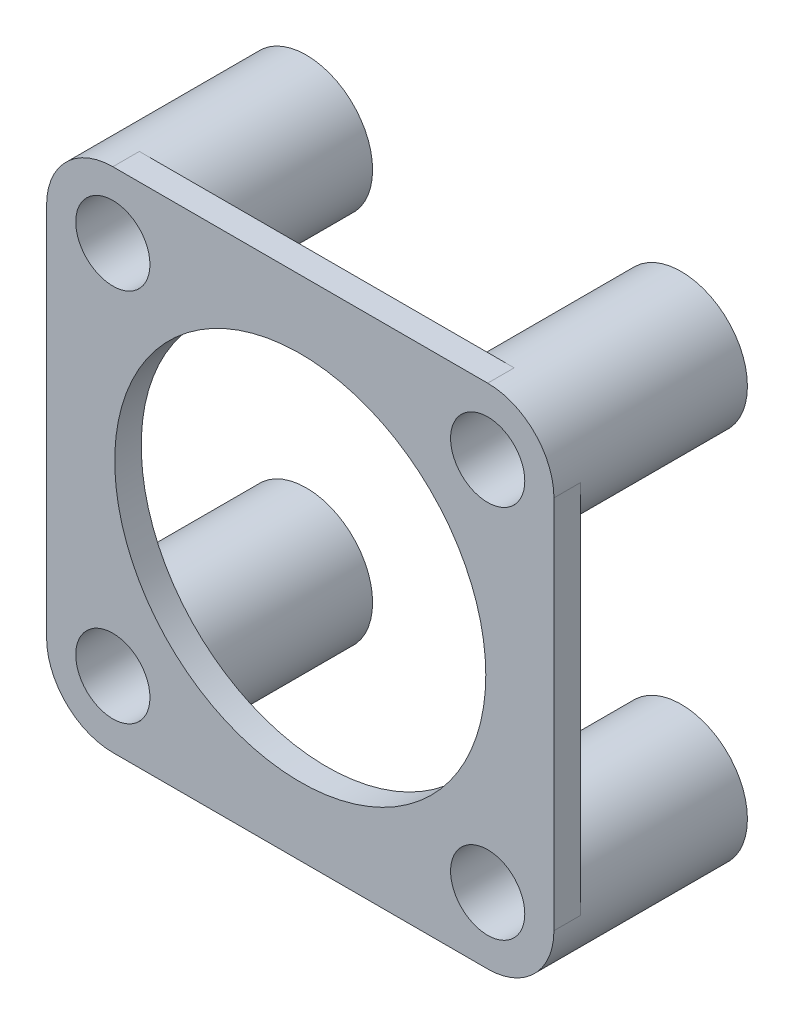
SolidWorks part; units mm, degrees
ref_plane "Front Plane" through (0, 0, 0) normal (0, 0, 1) x (1, 0, 0)
ref_plane "Top Plane" through (0, 0, 0) normal (0, 1, 0) x (1, 0, 0)
ref_plane "Right Plane" through (0, 0, 0) normal (1, 0, 0) x (0, 0, -1)
sketch "Sketch1" plane through (0, 0, 0) normal (0, 0, 1) x (1, 0, 0)
  line L1 (7.0711, -7.0711) -> (-7.0711, -7.0711) construction
  line L2 (7.0711, -7.0711) -> (7.0711, 7.0711) construction
  line L3 (7.0711, 7.0711) -> (-7.0711, 7.0711) construction
  line L4 (-7.0711, -7.0711) -> (-7.0711, 7.0711) construction
  line L5 (7.0711, -7.0711) -> (-7.0711, 7.0711) construction
  line L6 (7.0711, 7.0711) -> (-7.0711, -7.0711) construction
  circle A0 centre (-7.0711, 7.0711) radius 2.5
  circle A1 centre (7.0711, 7.0711) radius 2.5
  circle A2 centre (7.0711, -7.0711) radius 2.5
  circle A3 centre (-7.0711, -7.0711) radius 2.5
  circle A4 centre (-7.0711, 7.0711) radius 1.4
  circle A5 centre (7.0711, 7.0711) radius 1.4
  circle A6 centre (7.0711, -7.0711) radius 1.4
  circle A7 centre (-7.0711, -7.0711) radius 1.4
  point P0 (0, 0)
  dimension "D2" = 5
  dimension "D3" = 2.8
  dimension "D1" = 20
extrude "Boss-Extrude1" add sketch "Sketch1" along normal blind 6.3
sketch "Sketch2" plane through (0, 0, 6.3) normal (0, 0, 1) x (1, 0, 0)
  line L0 (-9.5711, 7.0711) -> (-9.5711, -7.0711)
  line L1 (-7.0711, -9.5711) -> (7.0711, -9.5711)
  line L2 (9.5711, -7.0711) -> (9.5711, 7.0711)
  line L3 (7.0711, 9.5711) -> (-7.0711, 9.5711)
  circle A0 centre (-7.0711, 7.0711) radius 2.5 construction
  circle A1 centre (-7.0711, -7.0711) radius 2.5 construction
  circle A2 centre (7.0711, -7.0711) radius 2.5 construction
  circle A3 centre (7.0711, 7.0711) radius 2.5 construction
  arc A4 (-9.5711, -7.0711) -> (-7.0711, -9.5711) centre (-7.0711, -7.0711) ccw
  arc A5 (7.0711, -9.5711) -> (9.5711, -7.0711) centre (7.0711, -7.0711) ccw
  arc A6 (9.5711, 7.0711) -> (7.0711, 9.5711) centre (7.0711, 7.0711) ccw
  arc A7 (-7.0711, 9.5711) -> (-9.5711, 7.0711) centre (-7.0711, 7.0711) ccw
  circle A8 centre (7.0711, -7.0711) radius 1.4 construction
  circle A9 centre (7.0711, 7.0711) radius 1.4 construction
  circle A10 centre (-7.0711, -7.0711) radius 1.4 construction
  circle A11 centre (-7.0711, 7.0711) radius 1.4 construction
  circle A12 centre (7.0711, -7.0711) radius 1.4
  circle A13 centre (7.0711, 7.0711) radius 1.4
  circle A14 centre (-7.0711, -7.0711) radius 1.4
  circle A15 centre (-7.0711, 7.0711) radius 1.4
  circle A16 centre (0, 0) radius 7
  dimension "D1" = 14
extrude "Boss-Extrude2" add sketch "Sketch2" along normal blind 1
